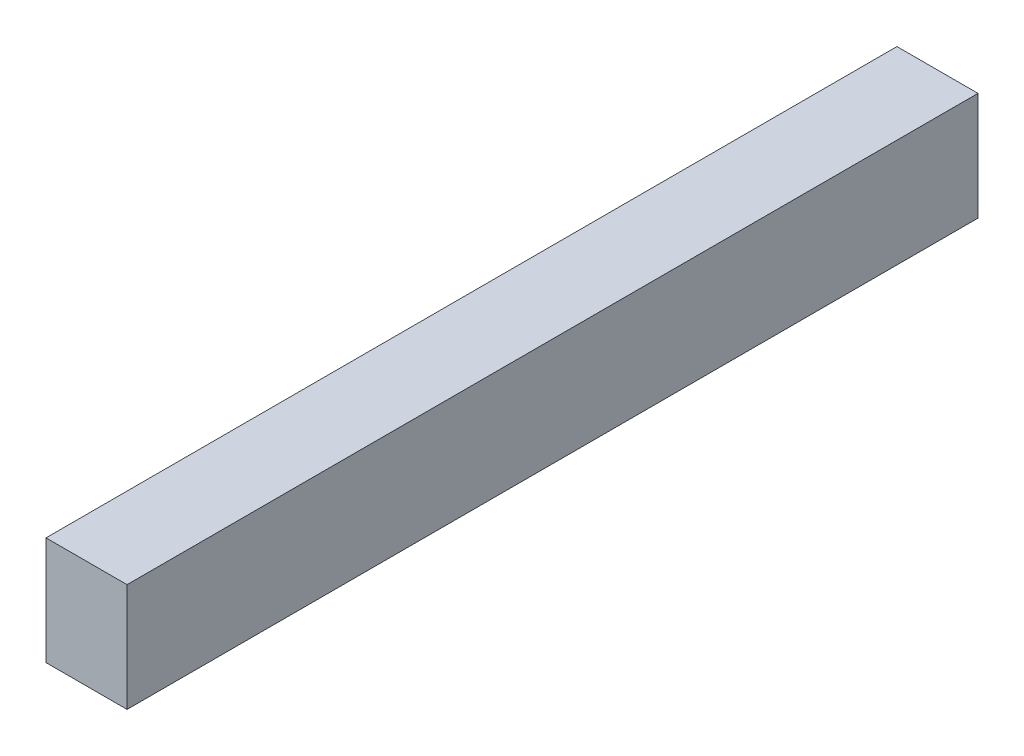
SolidWorks part; units mm, degrees
ref_plane "Front Plane" through (0, 0, 0) normal (0, 0, 1) x (1, 0, 0)
ref_plane "Top Plane" through (0, 0, 0) normal (0, 1, 0) x (1, 0, 0)
ref_plane "Right Plane" through (0, 0, 0) normal (1, 0, 0) x (0, 0, -1)
sketch "Sketch1" plane through (0, 0, 0) normal (0, 0, 1) x (1, 0, 0)
  line L1 (-13.4797, 10.8969) -> (-18.2422, 10.8969)
  line L2 (-13.4797, 10.8969) -> (-13.4797, 4.5469)
  line L3 (-13.4797, 4.5469) -> (-18.2422, 4.5469)
  line L4 (-18.2422, 10.8969) -> (-18.2422, 4.5469)
  dimension "D1" = 4.7625
  dimension "D2" = 6.35
extrude "Boss-Extrude1" add sketch "Sketch1" along normal blind 50
